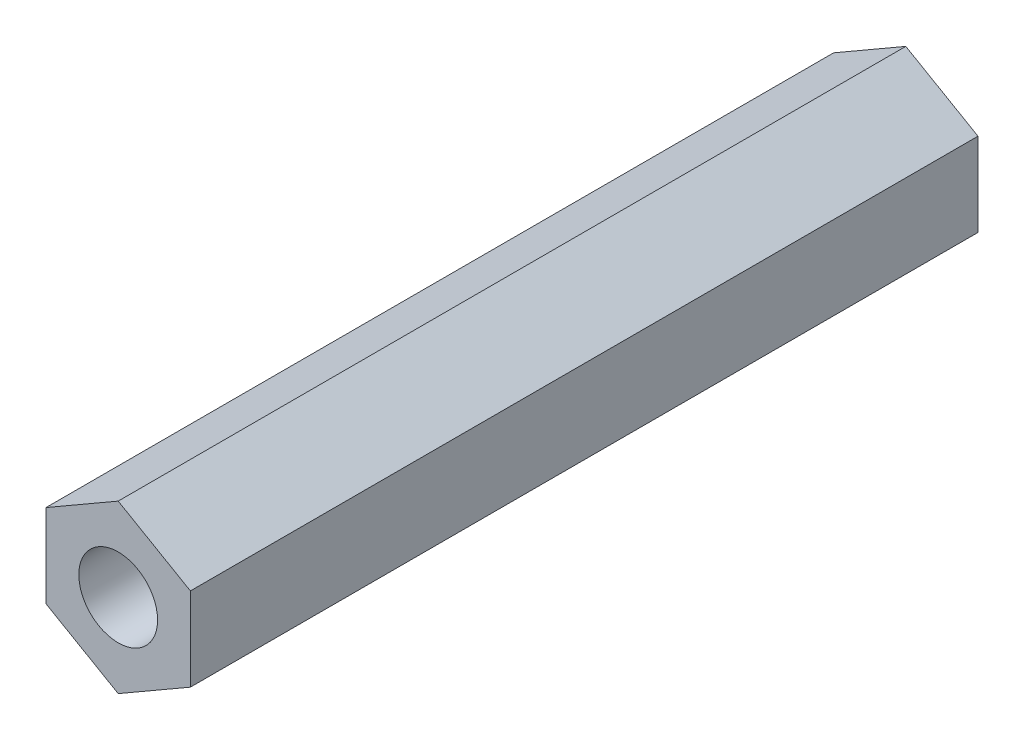
SolidWorks part; units mm, degrees
ref_plane "Plan de face" through (0, 0, 0) normal (0, 0, 1) x (1, 0, 0)
ref_plane "Plan de dessus" through (0, 0, 0) normal (0, 1, 0) x (1, 0, 0)
ref_plane "Plan de droite" through (0, 0, 0) normal (1, 0, 0) x (0, 0, -1)
sketch "Esquisse1" plane through (0, 0, 0) normal (0, 0, 1) x (1, 0, 0)
  line L1 (0, -3.1754) -> (2.75, -1.5877)
  line L2 (2.75, -1.5877) -> (2.75, 1.5877)
  line L3 (2.75, 1.5877) -> (0, 3.1754)
  line L4 (0, 3.1754) -> (-2.75, 1.5877)
  line L5 (-2.75, 1.5877) -> (-2.75, -1.5877)
  line L6 (-2.75, -1.5877) -> (0, -3.1754)
  circle A0 centre (0, 0) radius 2.75 construction
  circle A1 centre (0, 0) radius 1.5
  dimension "D2" = 3
  dimension "D1" = 5.5
extrude "Boss.-Extru.1" add sketch "Esquisse1" along normal blind 30
